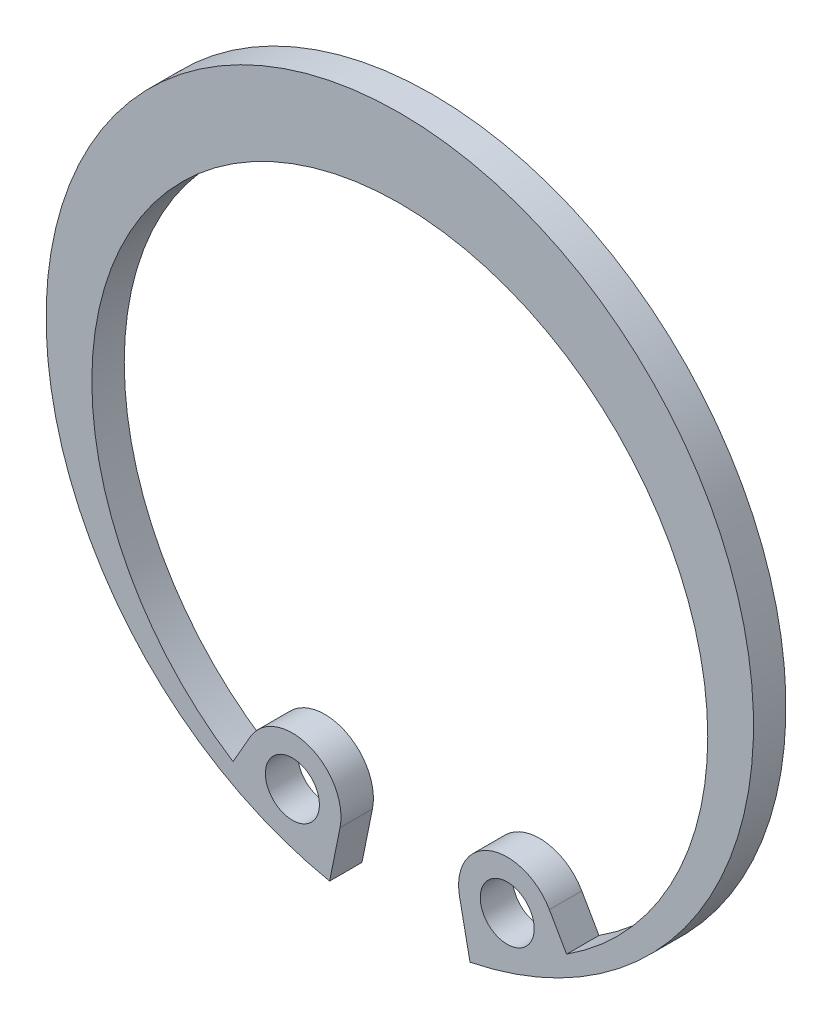
SolidWorks part; units mm, degrees
ref_plane "Plane1" through (0, 0, 0) normal (0, 0, 1) x (1, 0, 0)
ref_plane "Plane2" through (0, 0, 0) normal (0, 1, 0) x (1, 0, 0)
ref_plane "Plane3" through (0, 0, 0) normal (1, 0, 0) x (0, 0, -1)
extrude "Base-Extrude" add sketch "Sketch1" along normal blind 1.2
sketch "Sketch1" plane through (0, 0, 0) normal (0, 0, 1) x (1, 0, 0)
  line L0 (0, 0) -> (0, -1.2056) construction
  line L1 (0, 13.1) -> (0, 10.2) construction
  line L2 (-2.2141, -10.9338) -> (-2.6, -12.8394)
  line L3 (2.2141, -10.9338) -> (2.6, -12.8394)
  line L4 (6.1766, -10.7939) -> (5.5406, -9.6825)
  line L5 (-6.1766, -10.7939) -> (-5.5406, -9.6825)
  line L6 (0, 13.1) -> (0, 17.5) construction
  line L7 (0, 0) -> (5.5406, -9.6825) construction
  line L8 (2.2141, -10.9338) -> (0, 0) construction
  arc A0 (2.6, -12.8394) -> (-2.6, -12.8394) centre (0, 0) ccw
  arc A1 (6.1766, -10.7939) -> (-6.1766, -10.7939) centre (0, -1.2056) ccw
  arc A2 (2.2141, -10.9338) -> (5.5406, -9.6825) centre (3.9783, -10.5765) cw
  arc A3 (-2.2141, -10.9338) -> (-5.5406, -9.6825) centre (-3.9783, -10.5765) ccw
  circle A4 centre (3.9783, -10.5765) radius 1
  circle A5 centre (-3.9783, -10.5765) radius 1
  dimension "_d2" = 26.2
  dimension "_d5" = 2
  dimension "D8" = 1.8
  dimension "D9" = 22.8111
  dimension "D7" = 11.3
  dimension "b" = 2.9
  dimension "D4" = 5.2
  dimension "a" = 4.4
equation "\"D4@Sketch1\" = \"_d5@Sketch1\" * 2.6"
equation "\"D9@Sketch1\" = \"_d2@Sketch1\" - \"b@Sketch1\" - \"a@Sketch1\" / 9"
equation "\"D7@Sketch1\" = \"_d2@Sketch1\" / 2 - \"a@Sketch1\" + \"_d5@Sketch1\" * 1.3"
equation "\"D8@Sketch1\" = \"_d5@Sketch1\" * 0.9"
